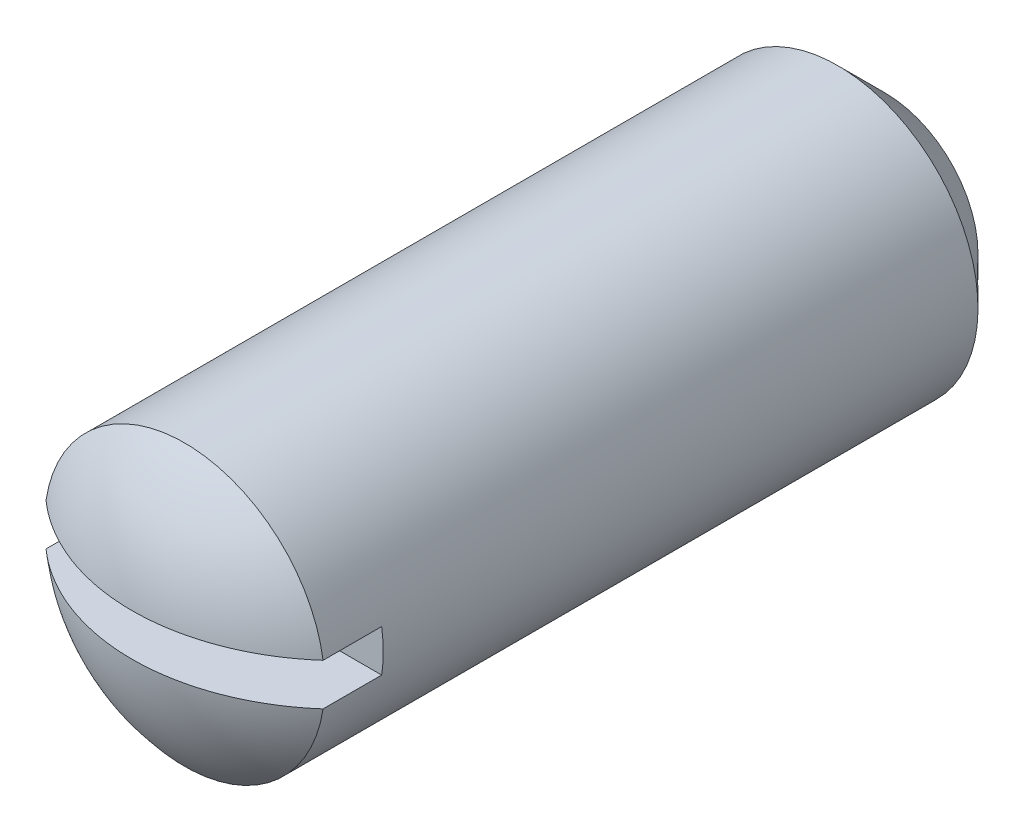
SolidWorks part; units mm, degrees
ref_plane "Спереди" through (0, 0, 0) normal (0, 0, 1) x (1, 0, 0)
ref_plane "Сверху" through (0, 0, 0) normal (0, 1, 0) x (1, 0, 0)
ref_plane "Справа" through (0, 0, 0) normal (1, 0, 0) x (0, 0, -1)
other "Configuration Table"
sketch "Эскиз1" plane through (0, 0, 0) normal (1, 0, 0) x (0, 0, -1)
  line L0 (-10, 0) -> (10, 0) construction
  line L1 (-10, 0) -> (-10, 4)
  line L2 (-10, 4) -> (10, 4)
  line L3 (10, 4) -> (10, 0)
  line L4 (-10, 4) -> (-5.5279, 0) construction
  line L5 (-11.5279, 0) -> (-10, 0)
  line L6 (10, 0) -> (-10, 0)
  arc A0 (-10, 4) -> (-11.5279, 0) centre (-5.5279, 0) ccw
  point P3 (0, 0)
  dimension "D3" = 6
  dimension "D1" = 8
  dimension "D2" = 20
revolve "Повернуть1" add sketch "Эскиз1" angle 360 about L6
cosmetic thread "Условное изображение резьбы1" parameters "D2"=5.3
chamfer "Фаска1" distance 1.35 angle 45 1 edges at (0, 4, -10)
sketch "Эскиз2" plane through (0, 0, 0) normal (1, 0, 0) x (0, 0, -1)
  line L0 (0, 0) -> (-10, 0) construction
  line L1 (-10, 4) -> (-10, -4) construction
  line L2 (-10, 0.6) -> (-10, -0.6)
  line L3 (-8.3279, -0.6) -> (-11.6721, -0.6)
  line L4 (-8.3279, -0.6) -> (-8.3279, 0.6)
  line L5 (-8.3279, 0.6) -> (-11.6721, 0.6)
  line L6 (-11.6721, -0.6) -> (-11.6721, 0.6)
  line L7 (-8.3279, -0.6) -> (-11.6721, 0.6) construction
  line L8 (-8.3279, 0.6) -> (-11.6721, -0.6) construction
  line L9 (-11.5279, 0) -> (-11.5279, 0.6)
  arc A0 (-10, 4) -> (-10, -4) centre (-5.5279, 0) ccw construction
  dimension "D1" = 3.2
  dimension "D2" = 0.6
extrude "Вырез-Вытянуть1" cut sketch "Эскиз2" against normal mid plane 10 contours L6 L3 L2 L5
